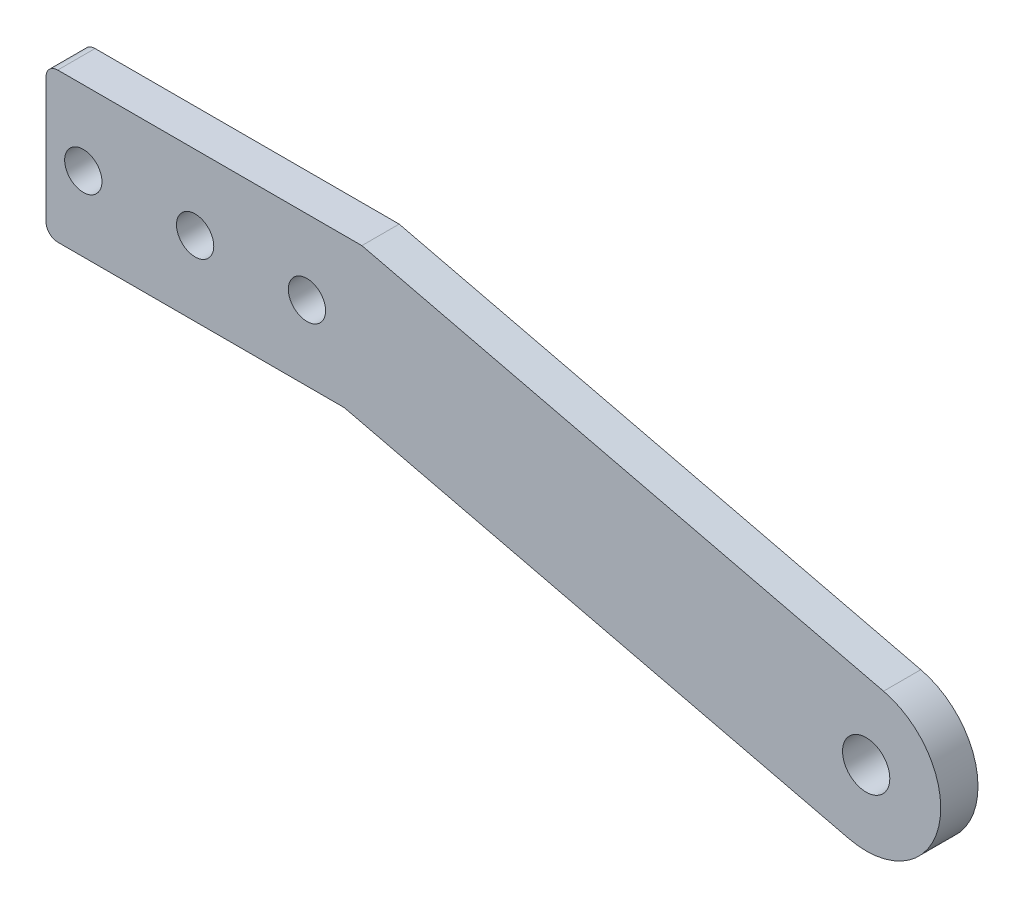
SolidWorks part; units mm, degrees
ref_plane "Front Plane" through (0, 0, 0) normal (0, 0, 1) x (1, 0, 0)
ref_plane "Top Plane" through (0, 0, 0) normal (0, 1, 0) x (1, 0, 0)
ref_plane "Right Plane" through (0, 0, 0) normal (1, 0, 0) x (0, 0, -1)
sketch "Sketch1" plane through (0, 0, 0) normal (0, 0, 1) x (1, 0, 0)
  line L0 (-25.4, 0) -> (-50.8, 0) construction
  line L2 (-50.8, -12.7) -> (-50.8, 12.7) construction
  line L5 (91.8604, -8.5999) -> (85.9396, -33.3001) construction
  line L6 (91.8604, -8.5999) -> (3.0017, 12.7)
  line L19 (-25.4, 0) -> (0, 0) construction
  line L25 (3.0017, 12.7) -> (-50.8, 12.7) construction
  line L26 (0, -12.7) -> (-50.8, -12.7) construction
  line L27 (0, -12.7) -> (85.9396, -33.3001)
  line L33 (-48.8, 12.7) -> (-48.8, -12.7) construction
  line L34 (-50.8, 10.7) -> (-50.8, -10.7)
  line L35 (-48.8, 12.7) -> (3.0017, 12.7)
  line L36 (-48.8, -12.7) -> (0, -12.7)
  line L37 (0, -12.7) -> (0, 12.7) construction
  circle A0 centre (-25.4, 0) radius 3.175
  circle A13 centre (88.9, -20.95) radius 4.025
  circle A16 centre (-44.45, 0) radius 3.175
  arc A17 (91.8604, -8.5999) -> (85.9396, -33.3001) centre (88.9, -20.95) cw
  arc A19 (-48.8, 12.7) -> (-50.8, 10.7) centre (-48.8, 10.7) ccw
  arc A20 (-48.8, -12.7) -> (-50.8, -10.7) centre (-48.8, -10.7) cw
  circle A21 centre (-6.35, 0) radius 3.175
  point P20 (-48.8, 10.7)
  point P21 (-48.8, -10.7)
  point P30 (0, 0)
  dimension "D4" = 6.35
  dimension "D7" = 19.05
  dimension "D10" = 25.4
  dimension "D5" = 25.4
  dimension "D6" = 20.95
  dimension "D9" = 8.05
  dimension "D2" = 88.9
  dimension "D3" = 25.4
  dimension "D12" = 19.05
  dimension "D13" = 25.4
  dimension "D14" = 2
  dimension "D15" = 2
  dimension "D16" = 2
extrude "Boss-Extrude1" add sketch "Sketch1" along normal blind 6.35
